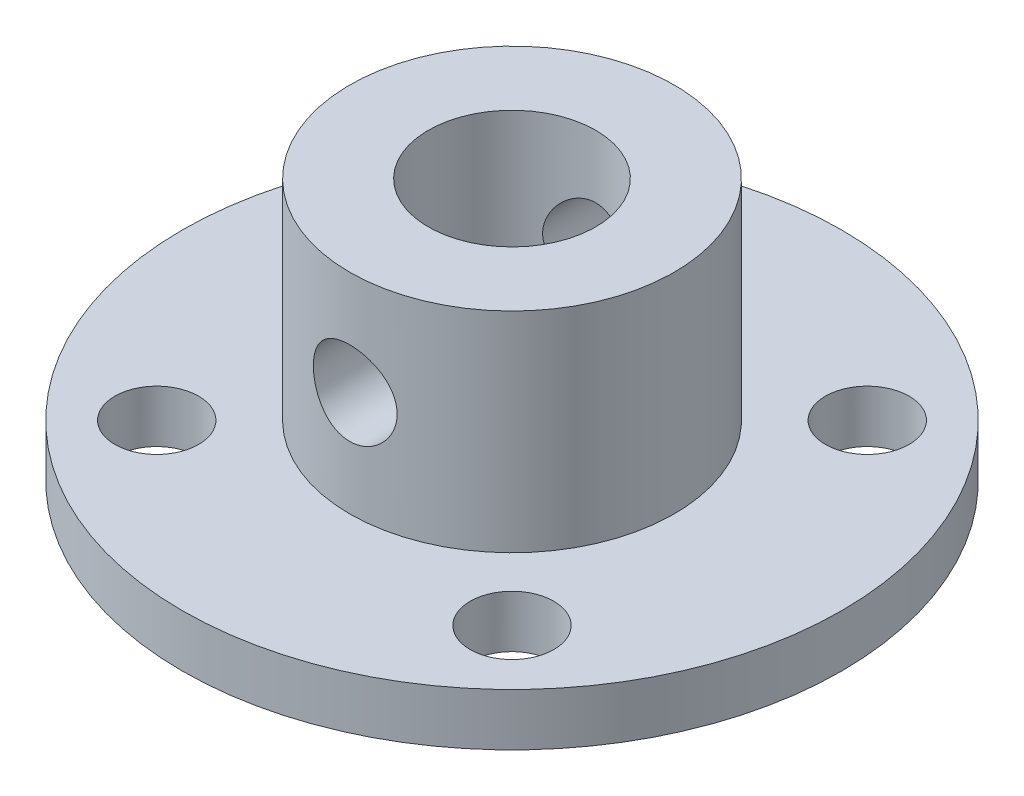
SolidWorks part; units mm, degrees
ref_plane "Front Plane" through (0, 0, 0) normal (0, 0, 1) x (1, 0, 0)
ref_plane "Top Plane" through (0, 0, 0) normal (0, 1, 0) x (1, 0, 0)
ref_plane "Right Plane" through (0, 0, 0) normal (1, 0, 0) x (0, 0, -1)
sketch "Sketch1" plane through (0, 0, 0) normal (0, 1, 0) x (1, 0, 0)
  circle A0 centre (0, 0) radius 15.75
  dimension "D1" = 31.5
extrude "Boss-Extrude1" add sketch "Sketch1" along normal blind 2.5
sketch "Sketch2" plane through (0, 2.5, 0) normal (0, 1, 0) x (1, 0, 0)
  circle A0 centre (0, 0) radius 7.75
  dimension "D1" = 15.5
extrude "Boss-Extrude2" add sketch "Sketch2" along normal blind 10
sketch "Sketch3" plane through (0, 0, 0) normal (0, -1, 0) x (1, 0, 0)
  circle A0 centre (0, 0) radius 4
  dimension "D1" = 8
extrude "Cut-Extrude1" cut sketch "Sketch3" against normal through all
sketch "Sketch4" plane through (0, 0, 0) normal (0, 0, 1) x (1, 0, 0)
  line L0 (0, 12.5) -> (0, 2.5) construction
  circle A0 centre (0, 7.5) radius 2
  dimension "D1" = 4
extrude "Cut-Extrude2" cut sketch "Sketch4" against normal through all and the other way through all
sketch "Sketch5" plane through (0, 0, 0) normal (0, -1, 0) x (1, 0, 0)
  line L0 (0, 0) -> (13.5384, 13.5384) construction
  line L1 (0, 0) -> (21.0597, 0) construction
  circle A0 centre (8.4853, 8.4853) radius 2
  circle A1 centre (8.4853, -8.4853) radius 2
  circle A2 centre (-8.4853, -8.4853) radius 2
  circle A3 centre (-8.4853, 8.4853) radius 2
  point P15 (0, 0)
  dimension "D3" = 4
  dimension "D1" = 45
  dimension "D2" = 12
  dimension "D4" = 4
extrude "Cut-Extrude3" cut sketch "Sketch5" against normal through all
sketch "Sketch6" plane through (0, 0, 0) normal (0, -1, 0) x (-1, 0, 0)
  line L0 (8.4853, -8.4853) -> (-8.4853, 8.4853) construction
  line L1 (-8.4853, -8.4853) -> (8.4853, 8.4853) construction
  line L2 (8.4853, 8.4853) -> (-8.4853, 8.4853) construction
  line L3 (8.4853, 8.4853) -> (8.4853, -8.4853) construction
